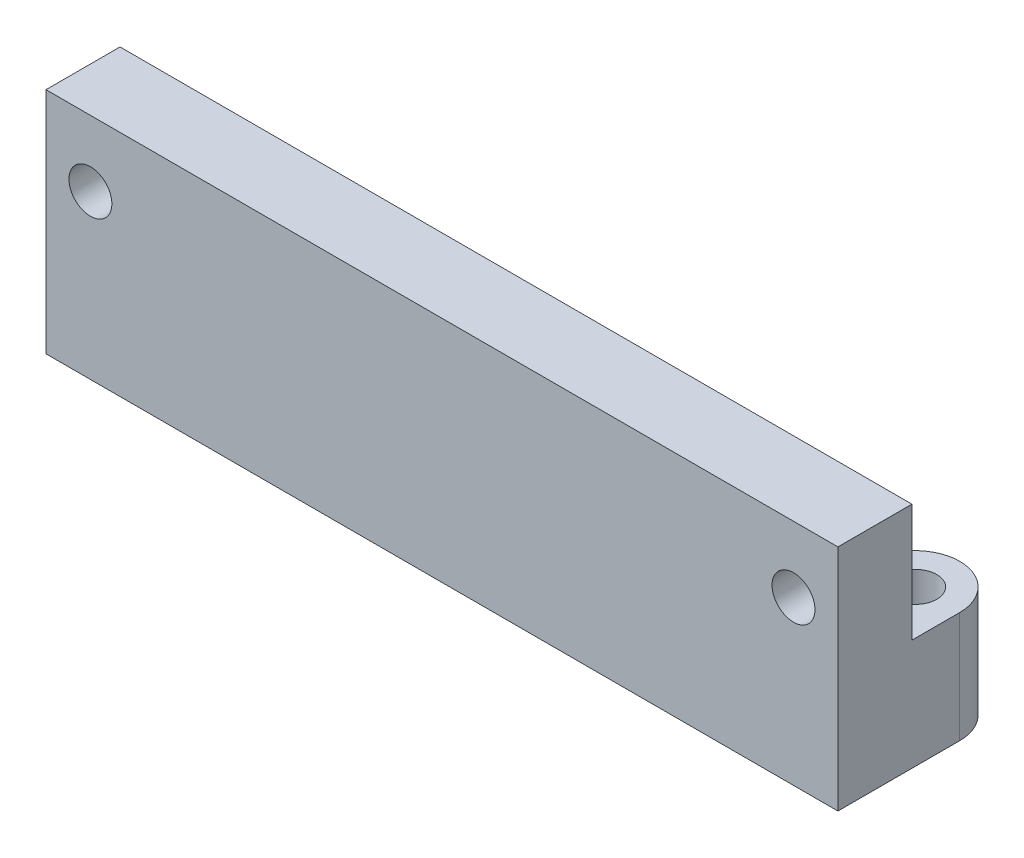
SolidWorks part; units mm, degrees
ref_plane "Front Plane" through (0, 0, 0) normal (0, 0, 1) x (1, 0, 0)
ref_plane "Top Plane" through (0, 0, 0) normal (0, 1, 0) x (1, 0, 0)
ref_plane "Right Plane" through (0, 0, 0) normal (1, 0, 0) x (0, 0, -1)
sketch "Sketch4" plane through (0, 0, 0) normal (0, 1, 0) x (1, 0, 0)
  line L0 (13.1849, 32.5004) -> (-93.8151, 32.5004)
  line L1 (-93.8151, 32.5004) -> (-93.8151, 48.9575)
  line L9 (13.1849, 32.5004) -> (13.1849, 48.9575)
  arc A2 (-81.8151, 48.9575) -> (-93.8151, 48.9575) centre (-87.8151, 48.9575) ccw
  arc A3 (13.1849, 48.9575) -> (1.1849, 48.9575) centre (7.1849, 48.9575) ccw
  arc A5 (-81.8151, 48.9575) -> (1.1849, 48.9575) centre (-40.3151, 179.0888) ccw
extrude "Boss-Extrude1" add sketch "Sketch4" along normal blind 15
sketch "Sketch5" plane through (0, 0, -32.5004) normal (0, 0, 1) x (1, 0, 0)
  line L0 (-93.8151, 15) -> (13.1849, 15)
  line L1 (13.1849, 15) -> (13.1849, 30.9109)
  line L2 (13.1849, 30.9109) -> (-93.8151, 30.9109)
  line L3 (-93.8151, 30.9109) -> (-93.8151, 15)
extrude "Boss-Extrude2" add sketch "Sketch5" against normal blind 10
sketch "Sketch6" plane through (0, 0, 0) normal (0, -1, 0) x (1, 0, 0)
  circle A0 centre (7.1849, -48.9575) radius 2.9
  circle A1 centre (-87.8151, -48.9575) radius 2.9
extrude "Cut-Extrude1" cut sketch "Sketch6" along normal blind 12.5 from surface at -15 starting at face at (-3.1277, 15, -46.8278)
sketch "Sketch7" plane through (0, 0, -42.5004) normal (0, 0, -1) x (-1, 0, 0)
  circle A0 centre (-7.1849, 22) radius 2.9
  circle A1 centre (87.8151, 22) radius 2.9
extrude "Cut-Extrude2" cut sketch "Sketch7" against normal blind 12.5
